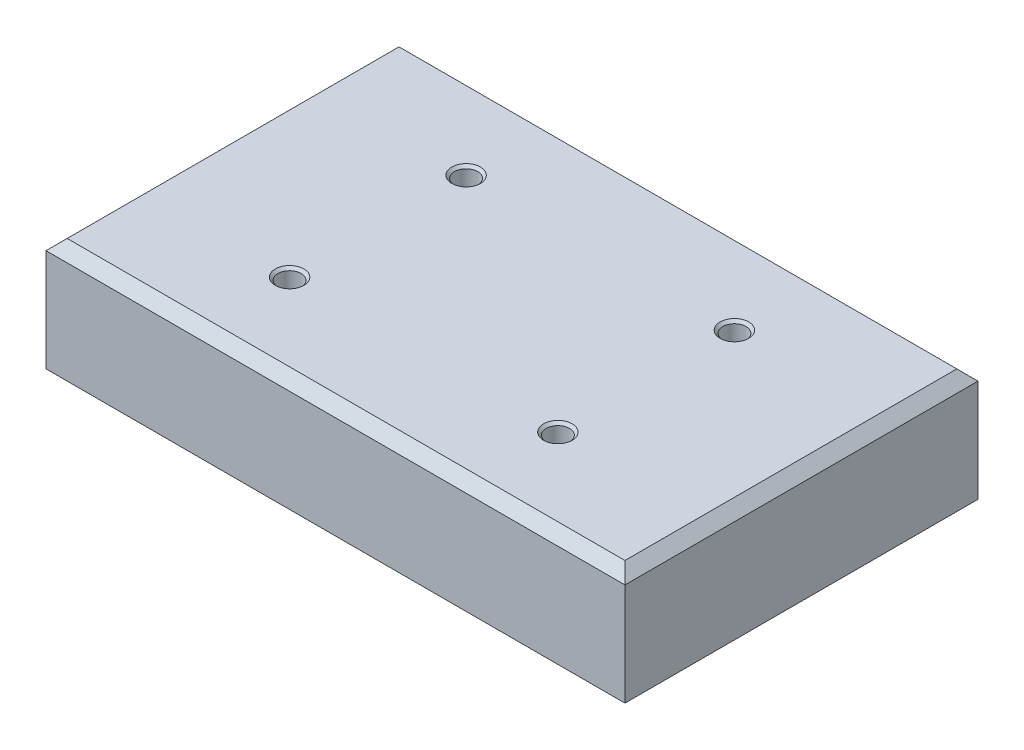
SolidWorks part; units mm, degrees
ref_plane "Front Plane" through (0, 0, 0) normal (0, 0, 1) x (1, 0, 0)
ref_plane "Top Plane" through (0, 0, 0) normal (0, 1, 0) x (1, 0, 0)
ref_plane "Right Plane" through (0, 0, 0) normal (1, 0, 0) x (0, 0, -1)
sketch "Sketch1" plane through (0, 0, 0) normal (0, 1, 0) x (1, 0, 0)
  line L1 (-41, -25) -> (41, -25)
  line L2 (-41, -25) -> (-41, 25)
  line L3 (-41, 25) -> (41, 25)
  line L4 (41, -25) -> (41, 25)
  line L5 (-41, -25) -> (41, 25) construction
  line L6 (-41, 25) -> (41, -25) construction
  point P0 (0, 0)
  dimension "D1" = 50
  dimension "D2" = 82
extrude "Boss-Extrude1" add sketch "Sketch1" along normal mid plane 16
chamfer "Chamfer1" distance 1.5 angle 45 4 edges at (41, 8, 0) (0, 8, -25) (-41, 8, 0) (0, 8, 25)
sketch "Sketch4" plane through (0, 8, 0) normal (0, 1, 0) x (1, 0, 0)
  line L0 (0, 23.5) -> (0, 0) construction
  line L1 (39.5, 23.5) -> (-39.5, 23.5) construction
  line L2 (0, 0) -> (-39.5, 0) construction
  line L3 (-39.5, 23.5) -> (-39.5, -23.5) construction
  point P0 (19, 12.5)
  point P2 (19, -12.5)
  point P4 (-19, -12.5)
  point P6 (-19, 12.5)
  dimension "D1" = 38
  dimension "D2" = 25
  dimension "D3" = 38
  dimension "D4" = 25
hole_wizard "M4 Tapped Hole1" positions "Sketch4" profile "Sketch5" tap size "M4" standard "DIN"
sketch "Sketch5" plane through (19, 8, -12.5) normal (1, 0, 0) x (0, 0, 1)
  line L0 (0, 0) -> (0, 8.9914)
  line L1 (0, 8.9914) -> (1.65, 8)
  line L2 (1.65, 8) -> (1.65, 0.375)
  line L3 (1.65, 0.375) -> (2.025, 0)
  line L5 (2.025, 0) -> (0, 0)
  line L6 (-1.65, 0.375) -> (-2.025, 0) construction
  line L10 (0, 8.9914) -> (-1.65, 8) construction
  line L11 (0, -6.35) -> (0, 107.95) construction
  dimension "Tap Drill Dia." = 3.3
  dimension "Tap Drill Depth" = 8
  dimension "Near C'Sink Dia." = 4.05
  dimension "Near C'Sink Angle" = 90
  dimension "Drill Angle" = 118
cosmetic thread "Hole Thread1" parameters "D1"=8, "D2"=4
cosmetic thread "Hole Thread2" parameters "D1"=8, "D2"=4
cosmetic thread "Hole Thread3" parameters "D1"=8, "D2"=4
cosmetic thread "Hole Thread4" parameters "D1"=8, "D2"=4
